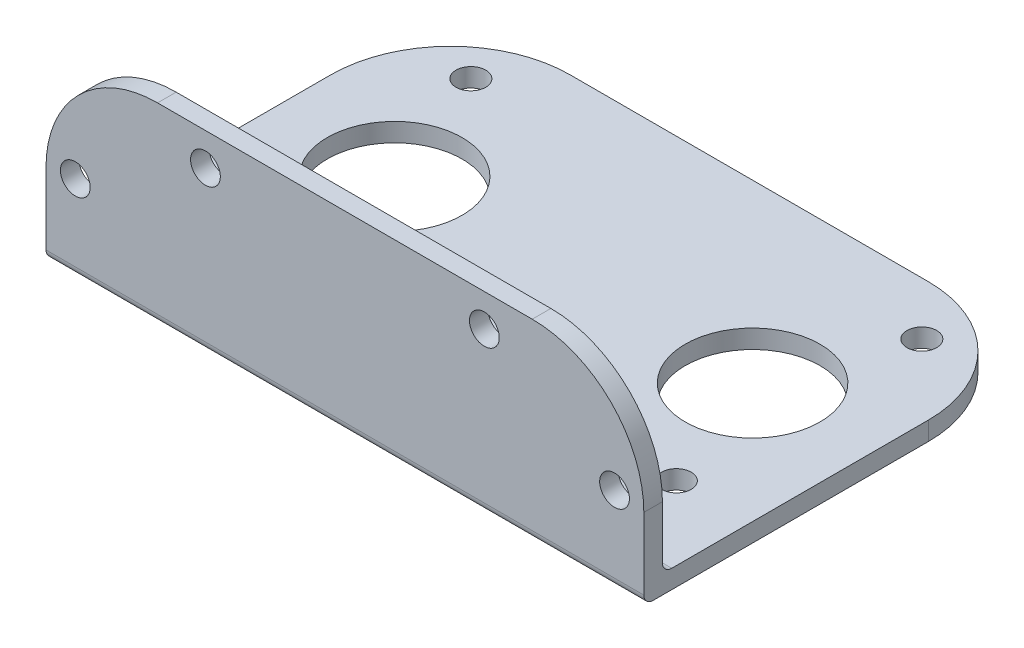
SolidWorks part; units mm, degrees
ref_plane "前视基准面" through (0, 0, 0) normal (0, 0, 1) x (1, 0, 0)
ref_plane "上视基准面" through (0, 0, 0) normal (0, 1, 0) x (1, 0, 0)
ref_plane "右视基准面" through (0, 0, 0) normal (1, 0, 0) x (0, 0, -1)
sketch "草图1" plane through (0, 0, 0) normal (0, 1, 0) x (1, 0, 0)
  line L0 (0, 0) -> (64.3, 0)
  line L1 (64.3, 0) -> (64.3, 30.6)
  line L2 (51.4, 43.5) -> (12.9, 43.5)
  line L4 (0, 30.6) -> (0, 0)
  line L5 (32.15, 0) -> (32.15, 43.5) construction
  arc A0 (64.3, 30.6) -> (51.4, 43.5) centre (51.4, 30.6) ccw
  arc A2 (12.9, 43.5) -> (0, 30.6) centre (12.9, 30.6) ccw
  circle A3 centre (7.8976, 11.4) radius 1.6
  circle A4 centre (7.8976, 37.8) radius 1.6
  circle A5 centre (12.9, 24.6) radius 7.25
  circle A6 centre (56.4024, 11.4) radius 1.6
  circle A7 centre (56.4024, 37.8) radius 1.6
  circle A8 centre (51.4, 24.6) radius 7.25
  dimension "D3" = 12.9
  dimension "D4" = 12.9
  dimension "D5" = 38.5
  dimension "D6" = 3.2
  dimension "D7" = 3.2
  dimension "D10" = 14.5
  dimension "D1" = 64.3
  dimension "D2" = 43.5
  dimension "D8" = 11.4
  dimension "D9" = 26.4
  dimension "D11" = 13.2
extrude "凸台-拉伸1" add sketch "草图1" along normal blind 2
sketch "草图2" plane through (0, 0, 0) normal (0, 0, 1) x (1, 0, 0)
  line L0 (0, 0) -> (0, 20.7)
  line L1 (64.3, 0) -> (64.3, 20.7)
  line L2 (64.3, 20.7) -> (0, 20.7)
  line L3 (32.15, 20.7) -> (32.15, 0) construction
  line L4 (0, 0) -> (64.3, 0) construction
  circle A0 centre (3.15, 9.2) radius 1.6
  circle A1 centre (17.15, 17.2) radius 1.6
  circle A2 centre (61.15, 9.2) radius 1.6
  circle A3 centre (47.15, 17.2) radius 1.6
  line M7 (64.3, 2) -> (0, 2)
  dimension "D2" = 3.2
  dimension "D3" = 3.2
  dimension "D1" = 20.7
  dimension "D4" = 9.2
  dimension "D5" = 8
  dimension "D6" = 29
  dimension "D7" = 15
extrude "凸台-拉伸2" add sketch "草图2" against normal blind 2 contours L3 L2 L0 A1 A0 M7 | L2 L3 L1 A3 A2 M7
fillet "圆角1" radius 12 2 edges at (0, 20.7, -1) (64.3, 20.7, -1)
fillet "圆角2" radius 1 2 edges at (32.15, 0, 0) (32.15, 2, -2)
